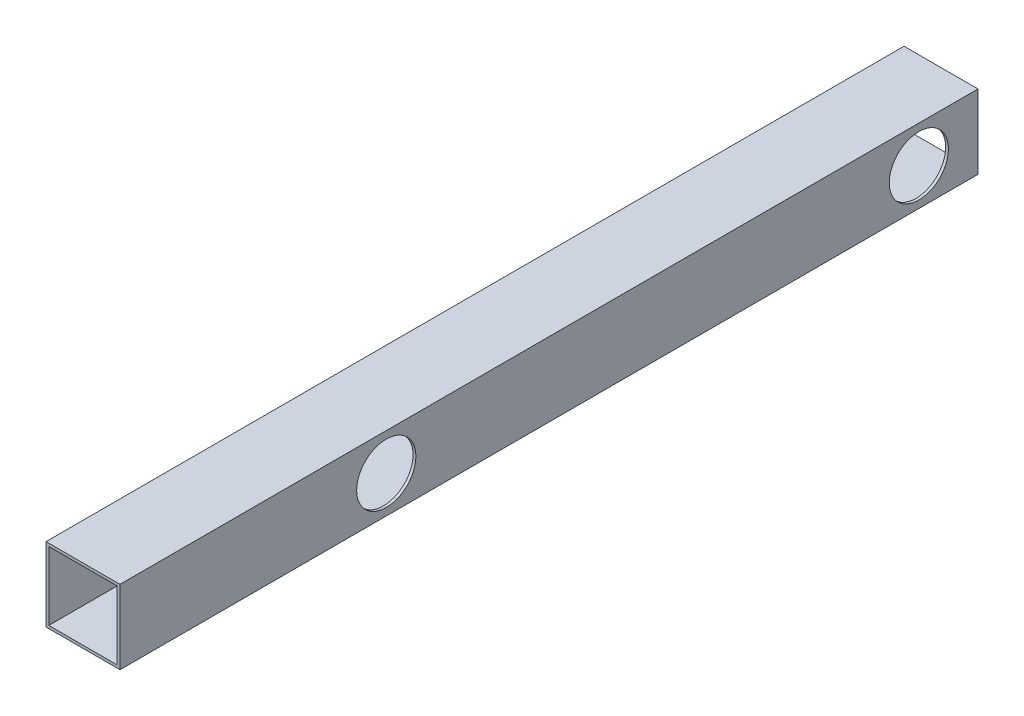
SolidWorks part; units mm, degrees
material "6061 Alloy"
ref_plane "Front Plane" through (0, 0, 0) normal (0, 0, 1) x (1, 0, 0)
ref_plane "Top Plane" through (0, 0, 0) normal (0, 1, 0) x (1, 0, 0)
ref_plane "Right Plane" through (0, 0, 0) normal (1, 0, 0) x (0, 0, -1)
sketch "Sketch1" plane through (0, 0, 0) normal (0, 0, 1) x (1, 0, 0)
  line L1 (-29.3688, -29.3688) -> (29.3688, -29.3688)
  line L2 (-29.3688, -29.3688) -> (-29.3688, 29.3688)
  line L3 (-29.3688, 29.3688) -> (29.3688, 29.3688)
  line L4 (29.3688, -29.3688) -> (29.3688, 29.3688)
  line L5 (-29.3688, -29.3688) -> (29.3688, 29.3688) construction
  line L6 (-29.3688, 29.3688) -> (29.3688, -29.3688) construction
  line L7 (-31.75, -31.75) -> (31.75, -31.75)
  line L8 (-31.75, -31.75) -> (-31.75, 31.75)
  line L9 (-31.75, 31.75) -> (31.75, 31.75)
  line L10 (31.75, -31.75) -> (31.75, 31.75)
  line L11 (-31.75, -31.75) -> (31.75, 31.75) construction
  line L12 (-31.75, 31.75) -> (31.75, -31.75) construction
  point P0 (0, 0)
  point P6 (0, 0)
  dimension "D1" = 2.3813
  dimension "D2" = 63.5
extrude "Boss-Extrude1" add sketch "Sketch1" along normal blind 431.8 and the other way blind 304.8
sketch "Sketch2" plane through (-31.75, 0, 0) normal (-1, 0, 0) x (0, 0, 1)
  line L0 (-254, 0) -> (0, 0) construction
  line L1 (0, 0) -> (203.2, 0) construction
  circle A0 centre (-254, 0) radius 25.4
  circle A1 centre (203.2, 0) radius 25.4
  dimension "D1" = 50.8
  dimension "D2" = 254
  dimension "D3" = 203.2
extrude "Cut-Extrude1" cut sketch "Sketch2" against normal through all
